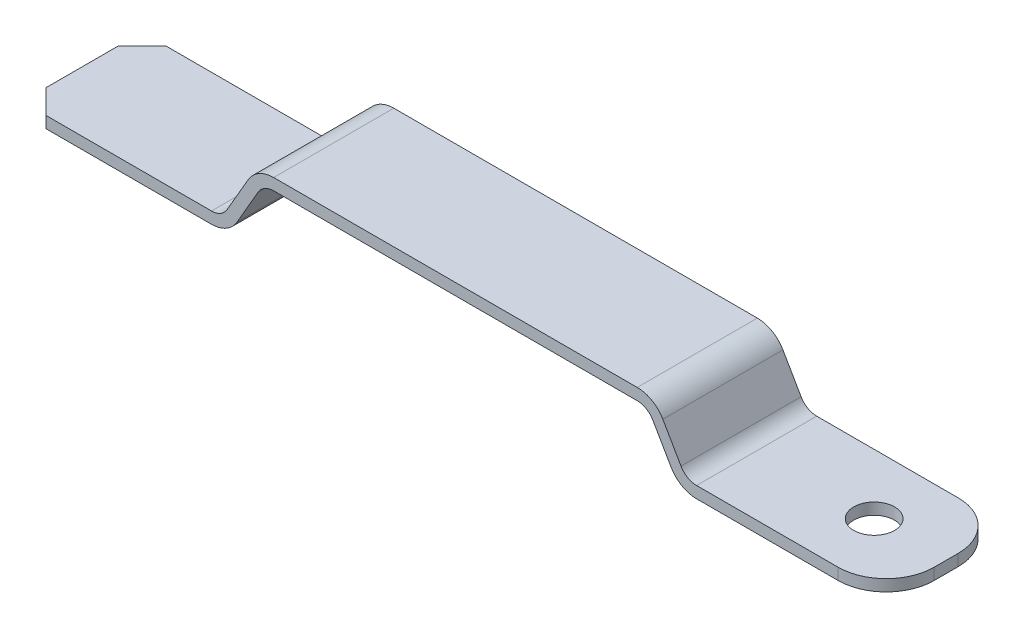
SolidWorks part; units mm, degrees
ref_plane "Front Plane" through (0, 0, 0) normal (0, 0, 1) x (1, 0, 0)
ref_plane "Top Plane" through (0, 0, 0) normal (0, 1, 0) x (1, 0, 0)
ref_plane "Right Plane" through (0, 0, 0) normal (1, 0, 0) x (0, 0, -1)
sketch "Sketch1" plane through (0, 0, 0) normal (0, 0, 1) x (1, 0, 0)
  line L0 (0, 22.6185) -> (0, -20.3983) construction
  line L1 (-43.2943, 0) -> (35.1535, 0) construction
  line L2 (-20.32, 0) -> (20.32, 0)
  line L3 (20.32, 0) -> (23.6929, -5.842)
  line L4 (23.6929, -5.842) -> (45.5369, -5.842)
  line L5 (-20.32, 0) -> (-23.9862, -6.35)
  line L6 (-23.9862, -6.35) -> (-45.8302, -6.35)
  dimension "D1" = 40.64
  dimension "D2" = 6.35
  dimension "D3" = 5.842
  dimension "D4" = 21.844
  dimension "D5" = 21.844
  dimension "D6" = 120
  dimension "D7" = 120
extrude "Extrude-Thin1" add sketch "Sketch1" along normal mid plane 12.7 thin thin type one direction wall 1.2192
fillet "Fillet1" radius 5.08 2 edges at (45.5369, -5.2324, -6.35) (45.5369, -5.2324, 6.35)
chamfer "Chamfer1" distance 2.54 angle 45 2 edges at (-45.8302, -5.7404, 6.35) (-45.8302, -5.7404, -6.35)
sketch "Sketch2" plane through (0, -4.6228, 0) normal (0, 1, 0) x (1, 0, 0)
  line L0 (40.4569, 6.35) -> (25.4966, 6.35) construction
  line L2 (45.5369, -1.27) -> (45.5369, 1.27) construction
  circle A0 centre (37.9169, 0) radius 2.159
  dimension "D1" = 4.318
  dimension "D2" = 6.35
  dimension "D3" = 7.62
extrude "Cut-Extrude1" cut sketch "Sketch2" against normal through all
